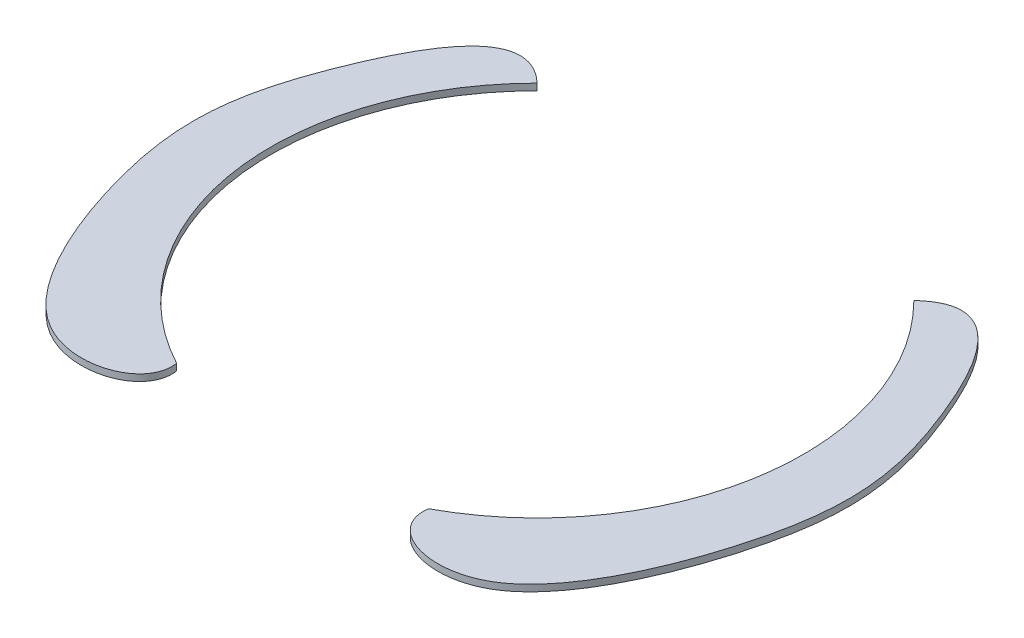
SolidWorks part; units mm, degrees
ref_plane "Front" through (0, 0, 0) normal (0, 0, 1) x (1, 0, 0)
ref_plane "Top" through (0, 0, 0) normal (0, 1, 0) x (1, 0, 0)
ref_plane "Right" through (0, 0, 0) normal (1, 0, 0) x (0, 0, -1)
sketch "Sketch1" plane through (0, 0, 0) normal (0, 1, 0) x (1, 0, 0)
  line L0 (-179.6051, 179.6051) -> (179.6051, 179.6051) construction
  line L1 (-179.6051, -334.4549) -> (179.6051, -334.4549) construction
  line L2 (-179.6051, -334.4549) -> (-179.6051, 334.4549) construction
  line L3 (-179.6051, 334.4549) -> (179.6051, 334.4549) construction
  line L4 (179.6051, -334.4549) -> (179.6051, 334.4549) construction
  line L5 (-179.6051, -334.4549) -> (179.6051, 334.4549) construction
  line L6 (-179.6051, 334.4549) -> (179.6051, -334.4549) construction
  line L7 (0, 0) -> (179.6051, 179.6051) construction
  line L8 (0, 0) -> (-179.6051, 179.6051) construction
  line L9 (0, 0) -> (0, -334.4549) construction
  arc A0 (-179.6051, 179.6051) -> (-120.1692, -223.7752) centre (0, 0) ccw
  arc A1 (120.1692, -223.7752) -> (179.6051, 179.6051) centre (0, 0) ccw
  spline S0 degree 3 poles (-179.6051, 179.6051) (-227.1851, 224.4535) (-311.1927, 68.2503) (-324.6609, -60.5382) (-224.9708, -297.6337) (-114.8024, -259.4227) (-120.1692, -223.7752) knots 0 0 0 0 0.234476 0.542617 0.775501 1 1 1 1
  spline S1 degree 3 poles (179.6051, 179.6051) (227.1851, 224.4535) (311.1927, 68.2503) (324.6609, -60.5382) (224.9708, -297.6337) (114.8024, -259.4227) (120.1692, -223.7752) knots 0 0 0 0 0.234476 0.542617 0.775501 1 1 1 1
  dimension "D1" = 90
  dimension "D2" = 508
extrude "Boss-Extrude1" add sketch "Sketch1" along normal blind 6.35
ref_plane "Plane3" through (0, -6.35, 0) normal (0, -1, 0) x (-1, 0, 0)
ref_plane "Plane1" through (0, 57.15, 0) normal (0, 1, 0) x (1, 0, 0)
